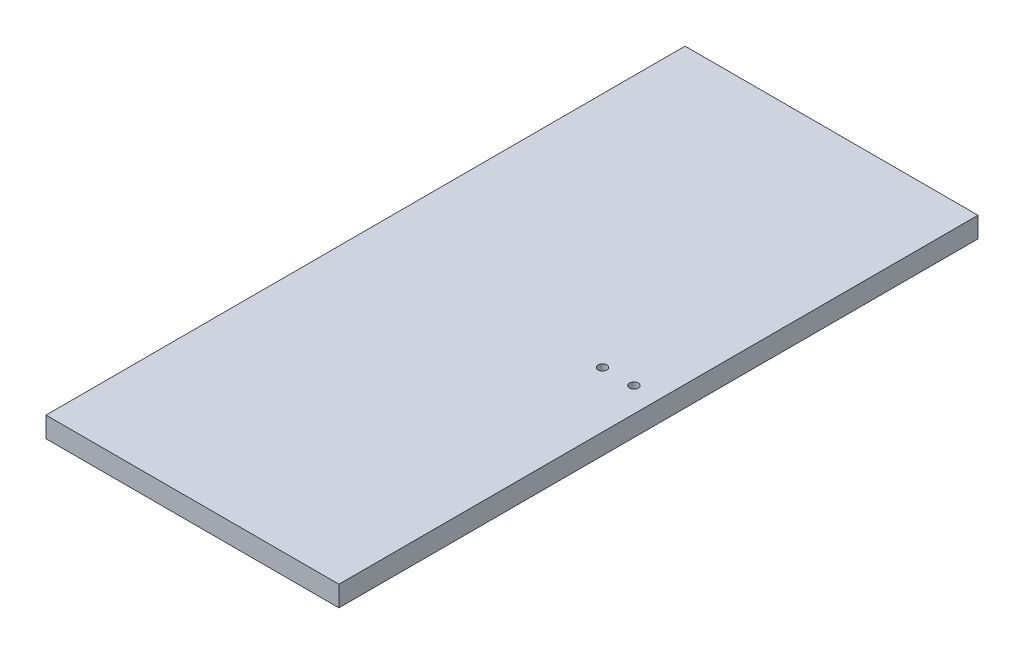
SolidWorks part; units mm, degrees
material "Maple"
ref_plane "Front Plane" through (0, 0, 0) normal (0, 0, 1) x (1, 0, 0)
ref_plane "Top Plane" through (0, 0, 0) normal (0, 1, 0) x (1, 0, 0)
ref_plane "Right Plane" through (0, 0, 0) normal (1, 0, 0) x (0, 0, -1)
sketch "Sketch1" plane through (0, 0, 0) normal (0, 0, 1) x (1, 0, 0)
  line L1 (0, 0) -> (139.7, 0)
  line L2 (0, 0) -> (0, 9.779)
  line L3 (0, 9.779) -> (139.7, 9.779)
  line L4 (139.7, 0) -> (139.7, 9.779)
  dimension "D1" = 9.779
  dimension "D2" = 139.7
extrude "Boss-Extrude1" add sketch "Sketch1" along normal blind 304.8
sketch "Sketch2" plane through (0, 9.779, 0) normal (0, 1, 0) x (1, 0, 0)
  line L0 (0, 0) -> (0, -152.4)
  line L1 (0, -304.8) -> (0, 0) construction
  line L2 (0, -152.4) -> (139.7, -152.4)
  line L3 (139.7, -304.8) -> (139.7, 0) construction
  line L4 (0, -152.4) -> (11.684, -152.4)
  line L5 (11.684, -152.4) -> (26.684, -152.4)
  line L6 (69.85, -152.4) -> (69.85, -52.2595)
  circle A0 centre (11.684, -152.4) radius 2.1
  circle A1 centre (26.684, -152.4) radius 2.1
  circle A2 centre (113.016, -152.4) radius 2.1
  circle A3 centre (128.016, -152.4) radius 2.1
  dimension "D3" = 4.2
  dimension "D4" = 4.2
  dimension "D1" = 11.684
  dimension "D2" = 15
extrude "Cut-Extrude2" cut sketch "Sketch2" against normal through all contours A2 L2 | A2 L2 | A3 L2 | A3 L2
